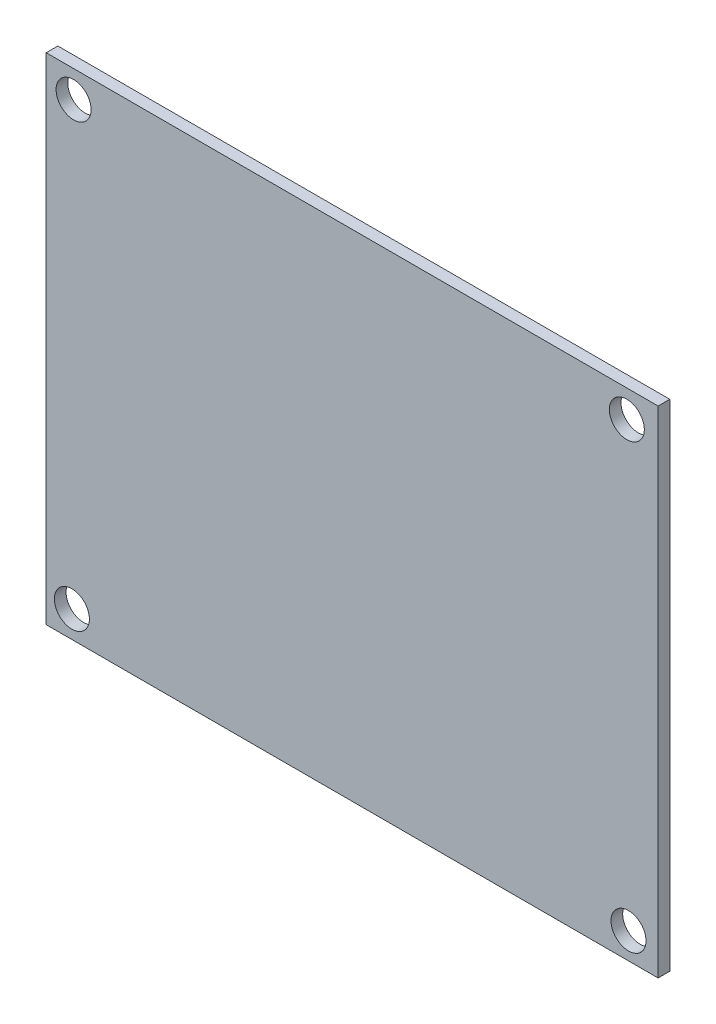
SolidWorks part; units mm, degrees
ref_plane "Front Plane" through (0, 0, 0) normal (0, 0, 1) x (1, 0, 0)
ref_plane "Top Plane" through (0, 0, 0) normal (0, 1, 0) x (1, 0, 0)
ref_plane "Right Plane" through (0, 0, 0) normal (1, 0, 0) x (0, 0, -1)
sketch "Sketch2" plane through (0, 0, 0) normal (0, 0, 1) x (1, 0, 0)
  line L1 (-48.2235, 33.6103) -> (56.7765, 33.6103)
  line L2 (-48.2235, 33.6103) -> (-48.2235, -51.3897)
  line L3 (-48.2235, -51.3897) -> (56.7765, -51.3897)
  line L4 (56.7765, 33.6103) -> (56.7765, -51.3897)
  circle A0 centre (-43.5259, 28.9851) radius 3.0034
  circle A1 centre (51.4073, 28.9296) radius 3.0034
  circle A2 centre (51.6959, -46.9145) radius 3.0034
  circle A3 centre (-43.8199, -46.8495) radius 3.0034
  point P10 (49.366, 10.0785)
  point P11 (50.9661, -33.0023)
  point P12 (51.6959, -46.9145)
  point P15 (-24.1356, -43.797)
  point P16 (-43.8199, -46.8495)
  dimension "D1" = 85
  dimension "D2" = 105
extrude "Boss-Extrude1" add sketch "Sketch2" along normal blind 2
